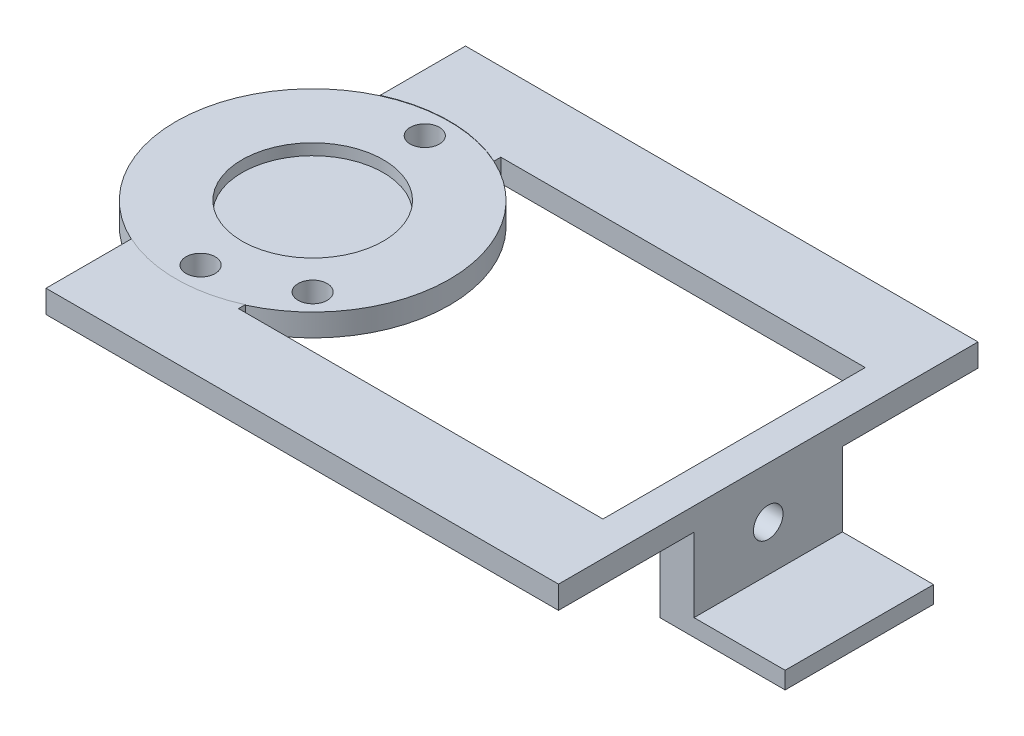
SolidWorks part; units mm, degrees
ref_plane "Front Plane" through (0, 0, 0) normal (0, 0, 1) x (1, 0, 0)
ref_plane "Top Plane" through (0, 0, 0) normal (0, 1, 0) x (1, 0, 0)
ref_plane "Right Plane" through (0, 0, 0) normal (1, 0, 0) x (0, 0, -1)
sketch "Sketch1" plane through (0, 0, 0) normal (0, 1, 0) x (1, 0, 0)
  circle A0 centre (0, 0) radius 30.5
extrude "Boss-Extrude1" add sketch "Sketch1" along normal blind 5
sketch "Sketch2" plane through (0, 5, 0) normal (0, 1, 0) x (1, 0, 0)
  circle A0 centre (0, 0) radius 15.75
extrude "Cut-Extrude1" cut sketch "Sketch2" against normal blind 2.5
sketch "Sketch3" plane through (0, 0, 0) normal (0, -1, 0) x (1, 0, 0)
  circle A0 centre (0, 0) radius 15.75
extrude "Boss-Extrude2" add sketch "Sketch3" along normal blind 2.5
sketch "Sketch4" plane through (0, 0, 0) normal (0, -1, 0) x (-1, 0, 0)
  circle A0 centre (0, 25) radius 3.25
  point P0 (0, 25)
  dimension "D1" = 25
extrude "Cut-Extrude2" cut sketch "Sketch4" against normal blind 5.08
sketch "Sketch5" plane through (0, 0, 0) normal (0, -1, 0) x (1, 0, 0)
  circle A0 centre (0, 25) radius 3.25
  point P0 (0, 25)
  dimension "D1" = 25
extrude "Cut-Extrude3" cut sketch "Sketch5" against normal blind 5.08
sketch "Sketch6" plane through (0, 0, 0) normal (0, -1, 0) x (1, 0, 0)
  circle A0 centre (0, 25) radius 3.25 construction
  circle A1 centre (17.6745, 17.6809) radius 3.25
  point P0 (17.6745, 17.6809)
  dimension "D1" = 25
  dimension "D2" = 19.13
extrude "Cut-Extrude4" cut sketch "Sketch6" against normal blind 5.08
sketch "Sketch7" plane through (0, 0, 0) normal (0, -1, 0) x (-1, 0, 0)
  line L0 (0, 0) -> (0, -30.5)
  line L1 (-12.7, -27.7301) -> (12.7, -27.7301)
  line L2 (-12.7, -27.7301) -> (-12.7, -46.7801)
  line L3 (-12.7, -46.7801) -> (12.7, -46.7801)
  line L4 (12.7, -27.7301) -> (12.7, -46.7801)
  circle A0 centre (0, 0) radius 30.5 construction
  circle M10 centre (0, 0) radius 30.5
  dimension "D1" = 25.4
  dimension "D2" = 12.7
  dimension "D3" = 19.05
extrude "Boss-Extrude3" add sketch "Sketch7" against normal blind 5.08 contours L4 L2 L3 M10
sketch "Sketch8" plane through (0, 0, 0) normal (0, -1, 0) x (1, 0, 0)
  line L0 (0, 0) -> (0, -30.5)
  line L1 (-12.7, -27.7301) -> (12.7, -27.7301)
  line L2 (-12.7, -27.7301) -> (-12.7, -46.7801)
  line L3 (-12.7, -46.7801) -> (12.7, -46.7801)
  line L4 (12.7, -27.7301) -> (12.7, -46.7801)
  arc A0 (-12.7, 27.7301) -> (12.7, 27.7301) centre (0, 0) ccw construction
  dimension "D1" = 25.4
  dimension "D2" = 12.7
  dimension "D3" = 19.05
extrude "Boss-Extrude4" add sketch "Sketch8" against normal blind 5.08
sketch "Sketch9" plane through (12.7, 0, 0) normal (1, 0, 0) x (0, 0, -1)
  line L0 (27.7301, 5.08) -> (46.7801, 5.08) construction
  line L1 (46.7801, 0) -> (29.2541, 0)
  line L2 (46.7801, 0) -> (46.7801, 5.08)
  line L3 (46.7801, 5.08) -> (29.2541, 5.08)
  line L4 (29.2541, 0) -> (29.2541, 5.08)
  dimension "D1" = 17.526
extrude "Boss-Extrude5" add sketch "Sketch9" along normal blind 106.68
sketch "Sketch10" plane through (12.7, 0, 0) normal (1, 0, 0) x (0, 0, -1)
  line L0 (-27.7301, 5.08) -> (-46.7801, 5.08) construction
  line L1 (-46.7801, 0) -> (-29.2541, 0)
  line L2 (-46.7801, 0) -> (-46.7801, 5.08)
  line L3 (-46.7801, 5.08) -> (-29.2541, 5.08)
  line L4 (-29.2541, 0) -> (-29.2541, 5.08)
  dimension "D1" = 17.526
extrude "Boss-Extrude6" add sketch "Sketch10" along normal blind 106.68
sketch "Sketch11" plane through (0, 0, 29.2541) normal (0, 0, -1) x (-1, 0, 0)
  line L0 (-119.38, 5.08) -> (-12.7, 5.08) construction
  line L1 (-119.38, 0) -> (-93.98, 0)
  line L2 (-119.38, 0) -> (-119.38, 5.08)
  line L3 (-119.38, 5.08) -> (-93.98, 5.08)
  line L4 (-93.98, 0) -> (-93.98, 5.08)
  dimension "D1" = 25.4
extrude "Boss-Extrude8" add sketch "Sketch11" along normal blind 63.5
sketch "Sketch14" plane through (119.38, 0, 0) normal (1, 0, 0) x (0, 0, -1)
  line L1 (46.7801, 0) -> (-46.7801, 0)
  line L2 (46.7801, 0) -> (46.7801, 5.08)
  line L3 (46.7801, 5.08) -> (-46.7801, 5.08)
  line L4 (-46.7801, 0) -> (-46.7801, 5.08)
extrude "Cut-Extrude6" cut sketch "Sketch14" against normal blind 17.78
sketch "Sketch15" plane through (0, 0, 0) normal (0, -1, 0) x (1, 0, 0)
  line L0 (93.98, -29.2541) -> (93.98, 29.2541) construction
  line L1 (93.98, -16.5541) -> (101.6, -16.5541)
  line L2 (93.98, -16.5541) -> (93.98, 16.5541)
  line L3 (93.98, 16.5541) -> (101.6, 16.5541)
  line L4 (101.6, -16.5541) -> (101.6, 16.5541)
  line L5 (101.6, 46.7801) -> (101.6, -46.7801) construction
  line L6 (93.98, -29.2541) -> (12.7, -29.2541) construction
  line L7 (93.98, 29.2541) -> (12.7, 29.2541) construction
  dimension "D1" = 12.7
  dimension "D2" = 12.7
extrude "Boss-Extrude10" add sketch "Sketch15" along normal blind 20.32
sketch "Sketch16" plane through (101.6, 0, 0) normal (1, 0, 0) x (0, 0, -1)
  line L0 (-16.5541, -20.32) -> (-16.5541, 0) construction
  line L1 (16.5541, -20.32) -> (-16.5541, -20.32)
  line L2 (16.5541, -20.32) -> (16.5541, -16.51)
  line L3 (16.5541, -16.51) -> (-16.5541, -16.51)
  line L4 (-16.5541, -20.32) -> (-16.5541, -16.51)
  dimension "D1" = 3.81
extrude "Boss-Extrude11" add sketch "Sketch16" along normal blind 20.32
sketch "Sketch17" plane through (93.98, 0, 0) normal (-1, 0, 0) x (0, 0, 1)
  line L0 (0, -20.32) -> (0, 5.08)
  line L1 (16.5541, -20.32) -> (-16.5541, -20.32) construction
  line L2 (-29.2541, 5.08) -> (29.2541, 5.08) construction
  circle A0 centre (0, -6.35) radius 3.302
  dimension "D1" = 13.97
extrude "Cut-Extrude7" cut sketch "Sketch17" against normal blind 7.62 contours L0 A0
sketch "Sketch18" plane through (93.98, 0, 0) normal (-1, 0, 0) x (0, 0, 1)
  circle A0 centre (0, -6.35) radius 4.826
extrude "Cut-Extrude8" cut sketch "Sketch18" against normal blind 2.54
